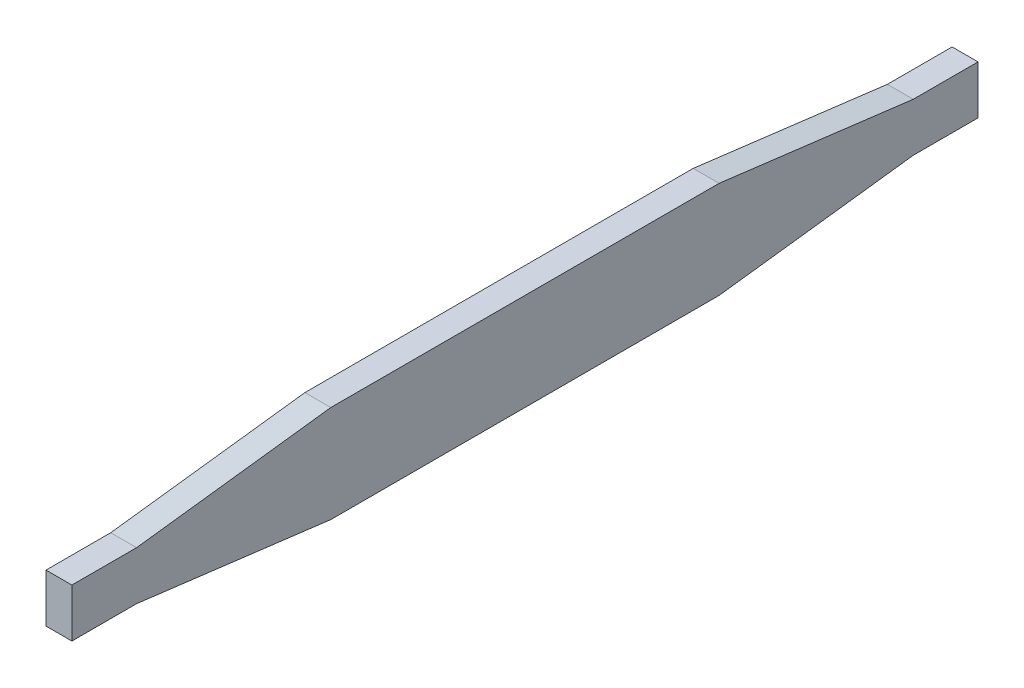
SolidWorks part; units mm, degrees
ref_plane "Спереди" through (0, 0, 0) normal (0, 0, 1) x (1, 0, 0)
ref_plane "Сверху" through (0, 0, 0) normal (0, 1, 0) x (1, 0, 0)
ref_plane "Справа" through (0, 0, 0) normal (1, 0, 0) x (0, 0, -1)
sketch "Эскиз1" plane through (0, 0, 0) normal (1, 0, 0) x (0, 0, -1)
  line L0 (30, 7.5) -> (60, 3.75)
  line L1 (-30, -7.5) -> (30, -7.5)
  line L2 (-30, -7.5) -> (-30, 7.5)
  line L3 (-30, 7.5) -> (30, 7.5)
  line L4 (30, -7.5) -> (30, 7.5)
  line L5 (-30, -7.5) -> (30, 7.5) construction
  line L6 (-30, 7.5) -> (30, -7.5) construction
  line L7 (60, -3.75) -> (70, -3.75)
  line L8 (60, -3.75) -> (60, 3.75)
  line L9 (60, 3.75) -> (70, 3.75)
  line L10 (70, -3.75) -> (70, 3.75)
  line L11 (60, -3.75) -> (70, 3.75) construction
  line L12 (60, 3.75) -> (70, -3.75) construction
  line L13 (60, -3.75) -> (30, -7.5)
  line L14 (0, 8.25) -> (0, -8.25) construction
  line L15 (-60, 3.75) -> (-70, -3.75) construction
  line L16 (-60, -3.75) -> (-70, 3.75) construction
  line L17 (-60, -3.75) -> (-30, -7.5)
  line L18 (-70, -3.75) -> (-70, 3.75)
  line L19 (-60, 3.75) -> (-70, 3.75)
  line L20 (-60, -3.75) -> (-60, 3.75)
  line L21 (-60, -3.75) -> (-70, -3.75)
  line L22 (-30, 7.5) -> (-60, 3.75)
  point P0 (0, 0)
  point P6 (65, 0)
  point P11 (64.4653, 0)
  point P18 (-65, 0)
  dimension "D1" = 60
  dimension "D2" = 15
  dimension "D3" = 7.5
  dimension "D4" = 10
  dimension "D5" = 30
extrude "Бобышка-Вытянуть1" add sketch "Эскиз1" along normal blind 4 contours L1 L4 L3 L2 | L2 L22 L20 L17 | L21 L20 L19 L18 | L13 L8 L0 L4 | L7 L10 L9 L8
